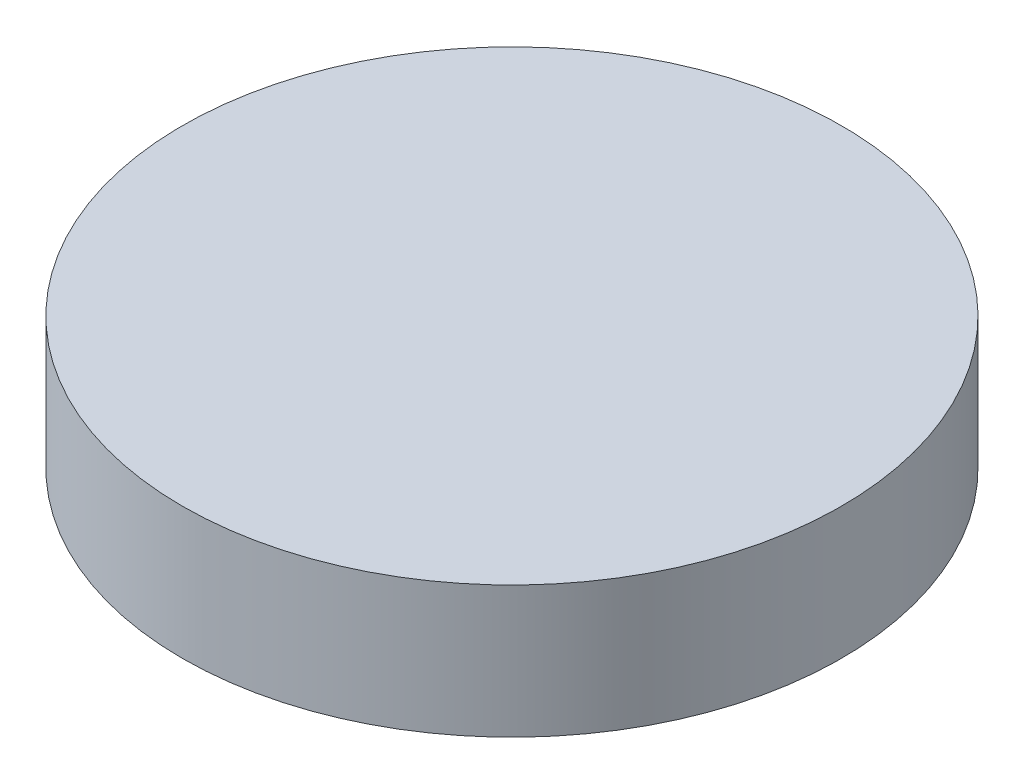
SolidWorks part; units mm, degrees
ref_plane "Front Plane" through (0, 0, 0) normal (0, 0, 1) x (1, 0, 0)
ref_plane "Top Plane" through (0, 0, 0) normal (0, 1, 0) x (1, 0, 0)
ref_plane "Right Plane" through (0, 0, 0) normal (1, 0, 0) x (0, 0, -1)
sketch "Sketch1" plane through (0, 0, 0) normal (0, 1, 0) x (1, 0, 0)
  circle A0 centre (0, 0) radius 12.5
  dimension "D1" = 25
extrude "Boss-Extrude1" add sketch "Sketch1" along normal blind 5
